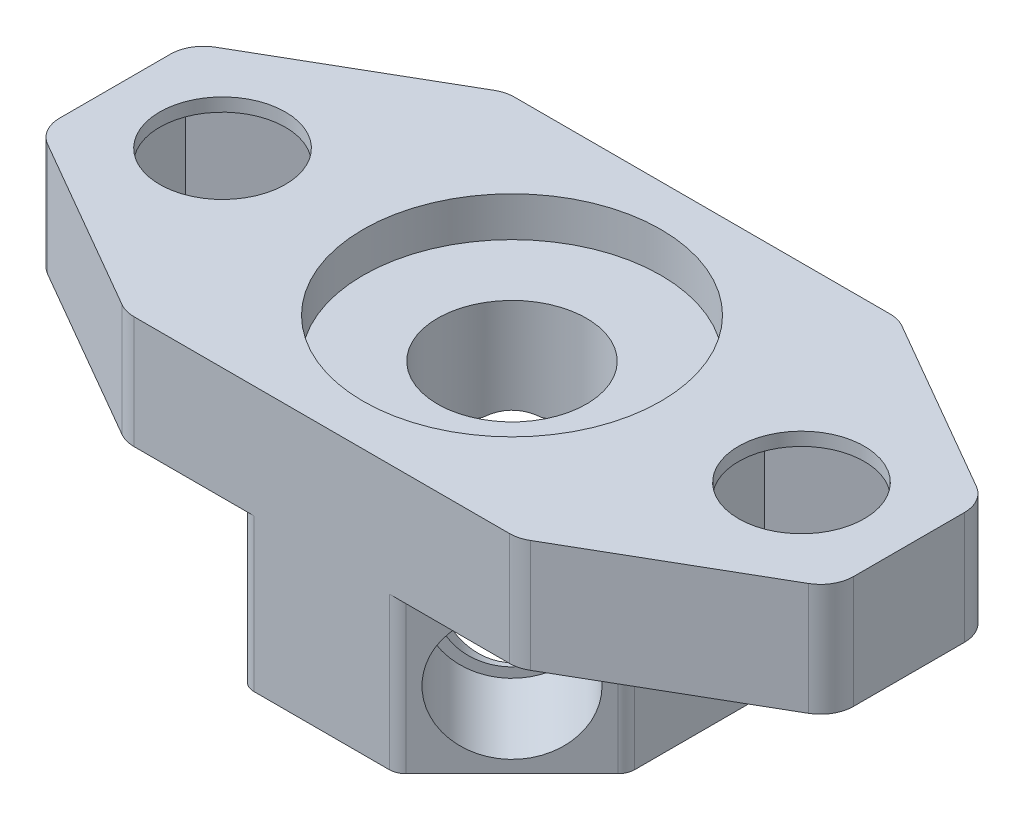
SolidWorks part; units mm, degrees
ref_plane "Plano frontal" through (0, 0, 0) normal (0, 0, 1) x (1, 0, 0)
ref_plane "Plano superior" through (0, 0, 0) normal (0, 1, 0) x (1, 0, 0)
ref_plane "Plano direito" through (0, 0, 0) normal (1, 0, 0) x (0, 0, -1)
sketch "Esboço10" plane through (0, 0, 0) normal (0, 1, 0) x (1, 0, 0)
  line L1 (-5.75, -5.75) -> (5.75, -5.75)
  line L2 (-5.75, -5.75) -> (-5.75, 5.75)
  line L3 (-5.75, 5.75) -> (5.75, 5.75)
  line L4 (5.75, -5.75) -> (5.75, 5.75)
  line L5 (-5.75, -5.75) -> (5.75, 5.75) construction
  line L6 (-5.75, 5.75) -> (5.75, -5.75) construction
  circle A0 centre (0, 0) radius 2.5
  dimension "D1" = 5
  dimension "D2" = 11.5
  dimension "D3" = 11.5
extrude "Ressalto-extrusão4" add sketch "Esboço10" along normal blind 8
chamfer "Chanfro2" distance 3.5 angle 45 4 edges at (5.75, 4, -5.75) (5.75, 4, 5.75) (-5.75, 4, -5.75) (-5.75, 4, 5.75)
sketch "Esboço12" plane through (-4, 0, 4) normal (-0.7071, 0, 0.7071) x (0.7071, 0, 0.7071)
  line L0 (2.4749, 0) -> (-2.4749, 0) construction
  circle A0 centre (0, 2.3) radius 1.925
  dimension "D1" = 3.85
  dimension "D2" = 2.3
extrude "Corte-extrusão4" cut sketch "Esboço12" against normal blind 3
sketch "Esboço17" plane through (4, 0, 4) normal (0.7071, 0, 0.7071) x (0.7071, 0, -0.7071)
  line L0 (2.4749, 0) -> (-2.4749, 0) construction
  circle A0 centre (0, 2.3) radius 1.925
  dimension "D1" = 3.85
  dimension "D2" = 2.3
extrude "Corte-extrusão5" cut sketch "Esboço17" against normal blind 3
mirror "Espelhar1" about plane through (0, 0, 0) normal (0, 0, 1) of "Corte-extrusão4"
mirror "Espelhar2" about plane through (0, 0, 0) normal (0, 0, 1) of "Corte-extrusão5"
sketch "Esboço18" plane through (0, 8, 0) normal (0, 1, 0) x (1, 0, 0)
  circle A0 centre (0, 0) radius 2.5
  circle A1 centre (0, 0) radius 2.25
  dimension "D1" = 5
  dimension "D2" = 4.5
extrude "Ressalto-extrusão5" add sketch "Esboço18" against normal blind 4.2
sketch "Esboço19" plane through (-1.8787, 0, 1.8787) normal (-0.7071, 0, 0.7071) x (0.7071, 0, 0.7071)
  circle A0 centre (0, 2.3) radius 1.625
  dimension "D1" = 3.25
extrude "Corte-extrusão6" cut sketch "Esboço19" against normal through all
sketch "Esboço20" plane through (1.8787, 0, 1.8787) normal (0.7071, 0, 0.7071) x (0.7071, 0, -0.7071)
  circle A0 centre (0, 2.3) radius 1.625
  dimension "D1" = 3.25
extrude "Corte-extrusão7" cut sketch "Esboço20" against normal through all
sketch "Esboço24" plane through (0, 8, 0) normal (0, 1, 0) x (1, 0, 0)
  line L0 (2.25, 5.75) -> (-2.25, 5.75) construction
  line L1 (12, -5.75) -> (-12, -5.75)
  line L2 (12, -5.75) -> (12, 5.75)
  line L3 (12, 5.75) -> (-12, 5.75)
  line L4 (-12, -5.75) -> (-12, 5.75)
  line L5 (12, -5.75) -> (-12, 5.75) construction
  line L6 (12, 5.75) -> (-12, -5.75) construction
  circle A0 centre (0, 0) radius 2.25
  point P0 (0, 0)
  dimension "D3" = 4.5
  dimension "D1" = 0
  dimension "D2" = 24
extrude "Ressalto-extrusão6" add sketch "Esboço24" against normal blind 3.4
sketch "Esboço25" plane through (0, 4.6, 0) normal (0, -1, 0) x (1, 0, 0)
  line L0 (0, 5.75) -> (0, -5.75) construction
  line L1 (-8.75, 3.06) -> (-11.4, 1.53)
  line L2 (-11.4, 1.53) -> (-11.4, -1.53)
  line L3 (-11.4, -1.53) -> (-8.75, -3.06)
  line L4 (-8.75, -3.06) -> (-6.1, -1.53)
  line L5 (-6.1, -1.53) -> (-6.1, 1.53)
  line L6 (-6.1, 1.53) -> (-8.75, 3.06)
  line L7 (-2.25, 5.75) -> (2.25, 5.75) construction
  line L8 (2.25, -5.75) -> (-2.25, -5.75) construction
  line L9 (6.1, 1.53) -> (8.75, 3.06)
  line L10 (6.1, -1.53) -> (6.1, 1.53)
  line L11 (8.75, -3.06) -> (6.1, -1.53)
  line L12 (11.4, -1.53) -> (8.75, -3.06)
  line L13 (11.4, 1.53) -> (11.4, -1.53)
  line L14 (8.75, 3.06) -> (11.4, 1.53)
  circle A0 centre (-8.75, 0) radius 2.65 construction
  circle A1 centre (8.75, 0) radius 2.65 construction
  dimension "D1" = 5.3
  dimension "D2" = 8.75
extrude "Corte-extrusão8" cut sketch "Esboço25" against normal blind 3
sketch "Esboço26" plane through (0, 7.6, 0) normal (0, -1, 0) x (1, 0, 0)
  line L0 (0, -5.75) -> (0, 5.75) construction
  line L1 (2.25, -5.75) -> (-2.25, -5.75) construction
  line L2 (-2.25, 5.75) -> (2.25, 5.75) construction
  circle A0 centre (-8.75, 0) radius 1.9
  circle A1 centre (8.75, 0) radius 1.9
  dimension "D1" = 3.8
extrude "Corte-extrusão9" cut sketch "Esboço26" against normal through all
sketch "Esboço27" plane through (0, 4.6, 0) normal (0, -1, 0) x (1, 0, 0)
  line L0 (-12, 5.75) -> (-12, 2.25)
  line L1 (-12, -5.75) -> (-12, 5.75) construction
  line L2 (-12, 2.25) -> (-5.9378, 5.75)
  line L3 (-12, 5.75) -> (-2.25, 5.75) construction
  line L4 (-5.9378, 5.75) -> (-12, 5.75)
  line L5 (-8.75, 3.06) -> (-11.4, 1.53) construction
  line L6 (0, 5.75) -> (0, -5.75) construction
  line L7 (-2.25, 5.75) -> (2.25, 5.75) construction
  line L8 (2.25, -5.75) -> (-2.25, -5.75) construction
  line L9 (-12, 0) -> (12, 0) construction
  line L10 (12, 5.75) -> (12, -5.75) construction
  line L11 (-5.9378, -5.75) -> (-12, -5.75)
  line L12 (-12, -2.25) -> (-5.9378, -5.75)
  line L13 (-12, -5.75) -> (-12, -2.25)
  line L14 (12, -5.75) -> (12, -2.25)
  line L15 (12, -2.25) -> (5.9378, -5.75)
  line L16 (5.9378, -5.75) -> (12, -5.75)
  line L17 (5.9378, 5.75) -> (12, 5.75)
  line L18 (12, 2.25) -> (5.9378, 5.75)
  line L19 (12, 5.75) -> (12, 2.25)
  dimension "D1" = 0
  dimension "D2" = 3.5
extrude "Corte-extrusão10" cut sketch "Esboço27" against normal through all
fillet "Filete3" radius 1 8 edges at (5.9378, 6.3, 5.75) (12, 6.3, 2.25) (12, 6.3, -2.25) (5.9378, 6.3, -5.75) (-5.9378, 6.3, -5.75) (-5.9378, 6.3, 5.75) (-12, 6.3, -2.25) (-12, 6.3, 2.25)
fillet "Filete4" radius 0.5 8 edges at (-5.75, 2.3, -2.25) (-2.25, 2.3, -5.75) (2.25, 2.3, -5.75) (5.75, 2.3, -2.25) (5.75, 2.3, 2.25) (2.25, 2.3, 5.75) (-5.75, 2.3, 2.25) (-2.25, 2.3, 5.75)
sketch "Esboço30" plane through (0, 8, 0) normal (0, 1, 0) x (1, 0, 0)
  circle A0 centre (0, 0) radius 4.5
  dimension "D1" = 9
extrude "Corte-extrusão11" cut sketch "Esboço30" against normal blind 1.2
